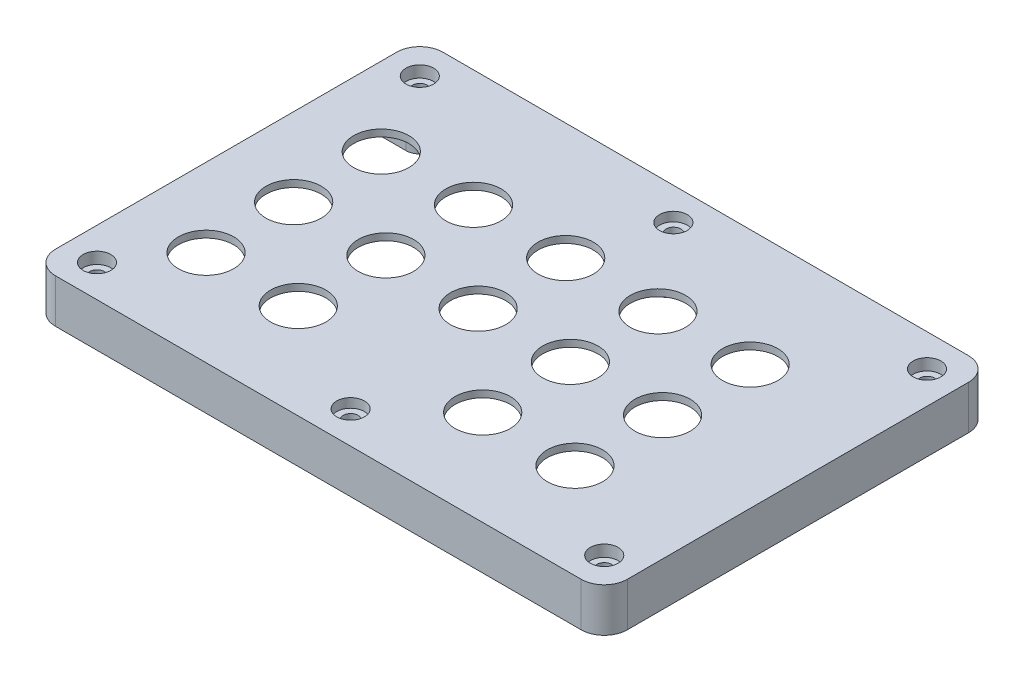
SolidWorks part; units mm, degrees
ref_plane "Front Plane" through (0, 0, 0) normal (0, 0, 1) x (1, 0, 0)
ref_plane "Top Plane" through (0, 0, 0) normal (0, 1, 0) x (1, 0, 0)
ref_plane "Right Plane" through (0, 0, 0) normal (1, 0, 0) x (0, 0, -1)
sketch "Sketch1" plane through (0, 0, 0) normal (0, 1, 0) x (1, 0, 0)
  line L1 (-482.8856, -32.0972) -> (-358.8856, -32.0972)
  line L2 (-482.8856, -32.0972) -> (-482.8856, -116.0972)
  line L3 (-482.8856, -116.0972) -> (-358.8856, -116.0972)
  line L4 (-358.8856, -32.0972) -> (-358.8856, -116.0972)
  dimension "D1" = 84
  dimension "D2" = 124
extrude "Boss-Extrude1" add sketch "Sketch1" along normal blind 9.5
sketch "Sketch2" plane through (0, 0, 0) normal (0, -1, 0) x (1, 0, 0)
  line L0 (-482.8856, 116.0972) -> (-358.8856, 116.0972) construction
  line L1 (-479.8856, 113.0972) -> (-361.8856, 113.0972)
  line L2 (-479.8856, 113.0972) -> (-479.8856, 35.0972)
  line L3 (-479.8856, 35.0972) -> (-361.8856, 35.0972)
  line L4 (-361.8856, 113.0972) -> (-361.8856, 35.0972)
  line L5 (-358.8856, 116.0972) -> (-358.8856, 32.0972) construction
  line L6 (-482.8856, 32.0972) -> (-482.8856, 116.0972) construction
  line L7 (-358.8856, 32.0972) -> (-482.8856, 32.0972) construction
  dimension "D1" = 3
  dimension "D2" = 3
  dimension "D3" = 3
  dimension "D4" = 3
extrude "Cut-Extrude1" cut sketch "Sketch2" against normal blind 8
fillet "Fillet1" radius 2 4 edges at (-479.8856, 4, 35.0972) (-479.8856, 4, 113.0972) (-361.8856, 4, 113.0972) (-361.8856, 4, 35.0972)
fillet "Fillet2" radius 5 4 edges at (-482.8856, 4.75, 116.0972) (-358.8856, 4.75, 116.0972) (-482.8856, 4.75, 32.0972) (-358.8856, 4.75, 32.0972)
sketch "Sketch3" plane through (0, 9.5, 0) normal (0, 1, 0) x (1, 0, 0)
  circle A0 centre (-465.8856, -57.4472) radius 6
  circle A1 centre (-445.8856, -57.4472) radius 6
  circle A2 centre (-425.8856, -57.4472) radius 6
  circle A3 centre (-405.8856, -57.4472) radius 6
  circle A4 centre (-385.8856, -57.4472) radius 6
  circle A5 centre (-465.8856, -76.4472) radius 6
  circle A6 centre (-445.8856, -76.4472) radius 6
  circle A7 centre (-425.8856, -76.4472) radius 6
  circle A8 centre (-405.8856, -76.4472) radius 6
  circle A9 centre (-385.8856, -76.4472) radius 6
  circle A10 centre (-465.8856, -95.4472) radius 6
  circle A11 centre (-445.8856, -95.4472) radius 6
  circle A13 centre (-405.8856, -95.4472) radius 6
  circle A14 centre (-385.8856, -95.4472) radius 6
  circle A15 centre (-425.8856, -95.4472) radius 6 [skipped]
  dimension "D1" = 12
  dimension "D2" = 5
  dimension "D3" = 3
extrude "Cut-Extrude2" cut sketch "Sketch3" against normal blind 2
sketch "Sketch4" plane through (0, 0, 32.0972) normal (0, 0, -1) x (-1, 0, 0)
  line L0 (363.8856, 0) -> (477.8856, 0) construction
  line L1 (375.8856, 0) -> (405.8856, 0)
  line L2 (375.8856, 0) -> (375.8856, 3.5)
  line L3 (375.8856, 3.5) -> (405.8856, 3.5)
  line L4 (405.8856, 0) -> (405.8856, 3.5)
  line L5 (482.8856, 9.5) -> (482.8856, 0) construction
  line L6 (435.8856, 0) -> (465.8856, 0)
  line L7 (435.8856, 0) -> (435.8856, 3.5)
  line L8 (435.8856, 3.5) -> (465.8856, 3.5)
  line L9 (465.8856, 0) -> (465.8856, 3.5)
  line L10 (358.8856, 0) -> (358.8856, 9.5) construction
  dimension "D1" = 3.5
  dimension "D2" = 3.5
  dimension "D3" = 17
  dimension "D4" = 30
  dimension "D5" = 30
  dimension "D6" = 17
extrude "Cut-Extrude3" cut sketch "Sketch4" against normal blind 4
sketch "Sketch5" plane through (0, 8, 0) normal (0, -1, 0) x (1, 0, 0)
  line L0 (-363.8856, 113.0972) -> (-477.8856, 113.0972) construction
  line L1 (-469.8856, 113.0972) -> (-479.8856, 113.0972)
  line L2 (-469.8856, 113.0972) -> (-469.8856, 103.0972)
  line L3 (-469.8856, 103.0972) -> (-479.8856, 103.0972)
  line L4 (-479.8856, 113.0972) -> (-479.8856, 103.0972)
  line L5 (-479.8856, 111.0972) -> (-479.8856, 37.0972) construction
  line L6 (-361.8856, 37.0972) -> (-361.8856, 111.0972) construction
  line L7 (-371.8856, 113.0972) -> (-361.8856, 113.0972)
  line L8 (-371.8856, 113.0972) -> (-371.8856, 103.0972)
  line L9 (-371.8856, 103.0972) -> (-361.8856, 103.0972)
  line L10 (-361.8856, 113.0972) -> (-361.8856, 103.0972)
  line L11 (-361.8856, 37.0972) -> (-361.8856, 111.0972) construction
  line L12 (-361.8856, 45.0972) -> (-371.8856, 45.0972)
  line L13 (-361.8856, 45.0972) -> (-361.8856, 35.0972)
  line L14 (-361.8856, 35.0972) -> (-371.8856, 35.0972)
  line L15 (-371.8856, 45.0972) -> (-371.8856, 35.0972)
  line L16 (-477.8856, 35.0972) -> (-363.8856, 35.0972) construction
  line L18 (-479.8856, 45.0972) -> (-469.8856, 45.0972)
  line L19 (-479.8856, 45.0972) -> (-479.8856, 35.0972)
  line L20 (-479.8856, 35.0972) -> (-469.8856, 35.0972)
  line L21 (-469.8856, 45.0972) -> (-469.8856, 35.0972)
  dimension "D1" = 10
  dimension "D2" = 10
  dimension "D3" = 10
  dimension "D4" = 10
  dimension "D5" = 10
  dimension "D6" = 10
  dimension "D7" = 10
  dimension "D8" = 10
extrude "Boss-Extrude2" add sketch "Sketch5" along normal up to surface (8 mm away) up to face at (-420.8856, 0, 65.9972)
fillet "Fillet3" radius 3 4 edges at (-469.8856, 4, 45.0972) (-469.8856, 4, 103.0972) (-371.8856, 4, 103.0972) (-371.8856, 4, 45.0972)
sketch "Sketch6" plane through (0, 0, 0) normal (0, -1, 0) x (1, 0, 0)
  circle A0 centre (-475.8856, 109.0972) radius 1.6
  circle A1 centre (-365.8856, 109.0972) radius 1.6
  circle A2 centre (-365.8856, 39.0972) radius 1.6
  circle A3 centre (-475.8856, 39.0972) radius 1.6
extrude "Cut-Extrude4" cut sketch "Sketch6" against normal up to surface (9.5 mm away) up to face at (-445.8856, 9.5, 63.4472)
sketch "Sketch7" plane through (0, 9.5, 0) normal (0, 1, 0) x (1, 0, 0)
  circle A0 centre (-365.8856, -39.0972) radius 3
  circle A1 centre (-365.8856, -109.0972) radius 3
  circle A2 centre (-475.8856, -109.0972) radius 3
  circle A3 centre (-475.8856, -39.0972) radius 3
  dimension "D1" = 6
  dimension "D2" = 6
  dimension "D3" = 6
  dimension "D4" = 6
extrude "Cut-Extrude5" cut sketch "Sketch7" against normal blind 2.5
sketch "Sketch8" plane through (0, 8, 0) normal (0, -1, 0) x (1, 0, 0)
  line L0 (-435.8856, 35.0972) -> (-405.8856, 35.0972) construction
  line L1 (-415.8856, 35.0972) -> (-425.8856, 35.0972)
  line L2 (-415.8856, 35.0972) -> (-415.8856, 45.0972)
  line L3 (-415.8856, 45.0972) -> (-425.8856, 45.0972)
  line L4 (-425.8856, 35.0972) -> (-425.8856, 45.0972)
  line L5 (-371.8856, 113.0972) -> (-469.8856, 113.0972) construction
  line L6 (-415.8856, 113.0972) -> (-425.8856, 113.0972)
  line L7 (-415.8856, 113.0972) -> (-415.8856, 103.0972)
  line L8 (-415.8856, 103.0972) -> (-425.8856, 103.0972)
  line L9 (-425.8856, 113.0972) -> (-425.8856, 103.0972)
  line L10 (-482.8856, 37.0972) -> (-482.8856, 111.0972) construction
  dimension "D1" = 10
  dimension "D2" = 57
  dimension "D3" = 10
  dimension "D4" = 10
  dimension "D5" = 10
  dimension "D6" = 57
extrude "Boss-Extrude3" add sketch "Sketch8" along normal up to surface (8 mm away) up to face at (-475.8856, 0, 37.4972)
fillet "Fillet4" radius 3 4 edges at (-425.8856, 4, 45.0972) (-415.8856, 4, 45.0972) (-425.8856, 4, 103.0972) (-415.8856, 4, 103.0972)
sketch "Sketch9" plane through (0, 0, 0) normal (0, -1, 0) x (1, 0, 0)
  circle A0 centre (-420.8856, 39.0972) radius 1.6
  circle A1 centre (-420.8856, 109.0972) radius 1.6
extrude "Cut-Extrude6" cut sketch "Sketch9" against normal up to surface (9.5 mm away) up to face at (-475.8856, 9.5, 42.0972)
sketch "Sketch10" plane through (0, 9.5, 0) normal (0, 1, 0) x (1, 0, 0)
  circle A0 centre (-420.8856, -109.0972) radius 3
  circle A1 centre (-420.8856, -39.0972) radius 3
  dimension "D1" = 6
  dimension "D2" = 6
extrude "Cut-Extrude7" cut sketch "Sketch10" against normal blind 2
